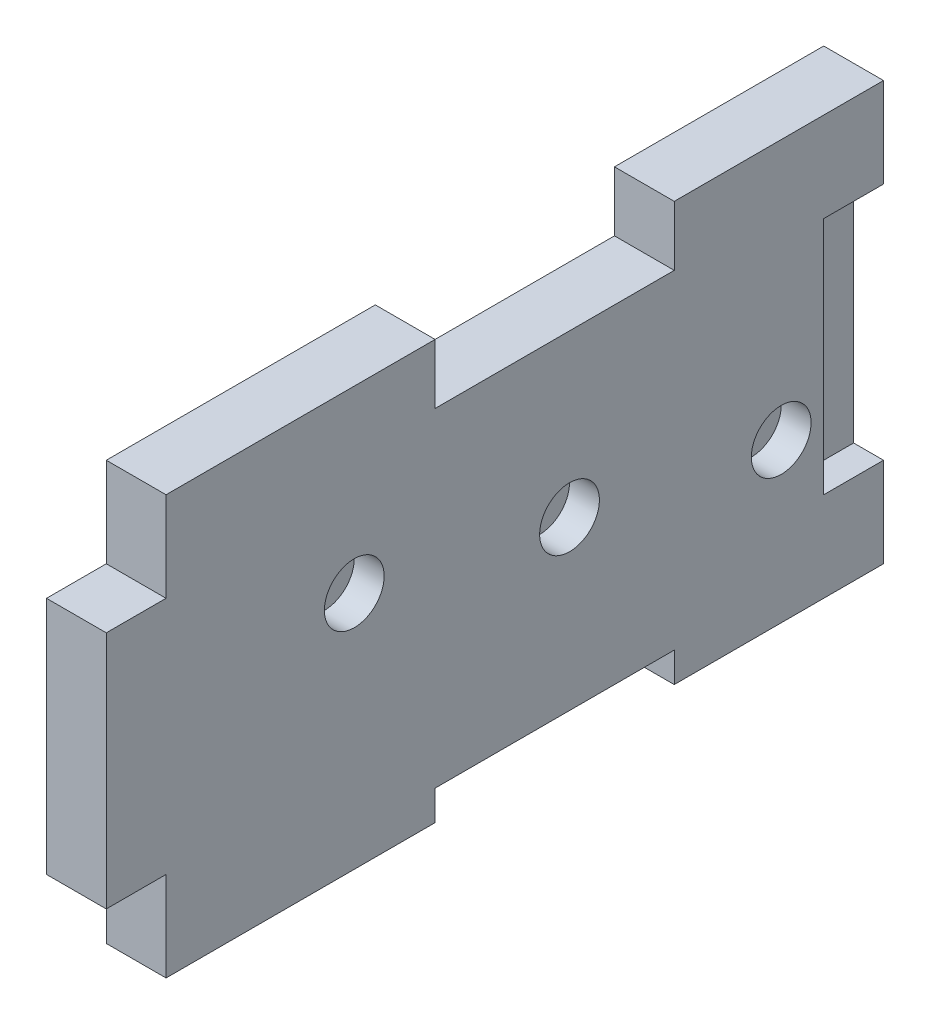
SolidWorks part; units mm, degrees
ref_plane "Front Plane" through (0, 0, 0) normal (0, 0, 1) x (1, 0, 0)
ref_plane "Top Plane" through (0, 0, 0) normal (0, 1, 0) x (1, 0, 0)
ref_plane "Right Plane" through (0, 0, 0) normal (1, 0, 0) x (0, 0, -1)
sketch "Sketch1" plane through (0, 0, 0) normal (1, 0, 0) x (0, 0, -1)
  line L1 (-130, 70) -> (0, 70)
  line L2 (-130, 70) -> (-130, 0)
  line L3 (-130, 0) -> (0, 0)
  line L4 (0, 70) -> (0, 0)
  line L5 (-130, 70) -> (-120, 70)
  line L6 (-130, 70) -> (-130, 55)
  line L7 (-130, 55) -> (-120, 55)
  line L8 (-120, 70) -> (-120, 55)
  line L9 (-130, 0) -> (-120, 0)
  line L10 (-130, 0) -> (-130, 15)
  line L11 (-130, 15) -> (-120, 15)
  line L12 (-120, 0) -> (-120, 15)
  line L13 (0, 70) -> (-10, 70)
  line L14 (0, 70) -> (0, 55)
  line L17 (0, 0) -> (-10, 0)
  line L18 (0, 0) -> (0, 15)
  line L21 (-75, 70) -> (-35, 70)
  line L22 (-75, 70) -> (-75, 60)
  line L23 (-75, 60) -> (-35, 60)
  line L24 (-35, 70) -> (-35, 60)
  line L25 (-75, 0) -> (-35, 0)
  line L26 (-75, 0) -> (-75, 5)
  line L27 (-75, 5) -> (-35, 5)
  line L28 (-35, 0) -> (-35, 5)
  dimension "D1" = 130
  dimension "D2" = 70
  dimension "D3" = 10
  dimension "D4" = 15
  dimension "D5" = 10
  dimension "D6" = 15
  dimension "D11" = 10
  dimension "D12" = 40
  dimension "D13" = 55
  dimension "D14" = 55
  dimension "D15" = 40
  dimension "D16" = 5
extrude "Boss-Extrude1" add sketch "Sketch1" along normal blind 5
sketch "Sketch2" plane through (5, 0, 0) normal (1, 0, 0) x (0, 0, -1)
  line L1 (-130, 55) -> (-130, 15) construction
  line L2 (-75, 5) -> (-35, 5) construction
  circle A0 centre (-88.52, 40) radius 5
  dimension "D3" = 10
  dimension "D1" = 35
  dimension "D2" = 41.48
sketch "Sketch5" plane through (0, 0, 0) normal (-1, 0, 0) x (0, 0, 1)
  line L0 (75, 5) -> (35, 5) construction
  line L1 (0, 70) -> (0, 0) construction
  line L3 (120, 70) -> (120, 55) construction
  circle A0 centre (52.52, 33) radius 5
  circle A1 centre (17.1117, 26.5) radius 5
  dimension "D1" = 10
  dimension "D4" = 10
  dimension "D6" = 17.1117
  dimension "D2" = 28
  dimension "D3" = 67.48
  dimension "D5" = 36
extrude "Cut-Extrude4" cut sketch "Sketch5" against normal blind 5 contours A1 | A0
extrude "Cut-Extrude5" cut sketch "Sketch2" against normal blind 5
sketch "Sketch6" plane through (0, 0, 0) normal (-1, 0, 0) x (0, 0, 1)
  line L40 (35, 0) -> (35, 5)
  line L41 (35, 5) -> (75, 5)
  line L42 (75, 5) -> (75, 0)
  line L43 (75, 0) -> (120, 0)
  line L44 (120, 0) -> (120, 15)
  line L45 (120, 15) -> (130, 15)
  line L46 (130, 15) -> (130, 55)
  line L47 (130, 55) -> (120, 55)
  line L48 (120, 55) -> (120, 70)
  line L49 (120, 70) -> (75, 70)
  line L50 (75, 70) -> (75, 60)
  line L51 (75, 60) -> (35, 60)
  line L52 (35, 60) -> (35, 70)
  line L53 (35, 70) -> (0, 70)
  line L56 (0, 70) -> (0, 0)
  line L59 (0, 0) -> (35, 0)
  line L60 (35, 0) -> (35, 5)
  line L61 (35, 5) -> (75, 5)
  line L62 (75, 5) -> (75, 0)
  line L63 (75, 0) -> (120, 0)
  line L64 (120, 0) -> (120, 15)
  line L65 (120, 15) -> (130, 15)
  line L66 (130, 15) -> (130, 55)
  line L67 (130, 55) -> (120, 55)
  line L68 (120, 55) -> (120, 70)
  line L69 (120, 70) -> (75, 70)
  line L70 (75, 70) -> (75, 60)
  line L71 (75, 60) -> (35, 60)
  line L72 (35, 60) -> (35, 70)
  line L73 (35, 70) -> (0, 70)
  line L76 (0, 70) -> (0, 0)
  line L79 (0, 0) -> (35, 0)
  dimension "D1" = 0
extrude "Boss-Extrude2" add sketch "Sketch6" along normal blind 5
sketch "Sketch7" plane through (5, 0, 0) normal (1, 0, 0) x (0, 0, -1)
  line L0 (0, 70) -> (0, 0) construction
  line L1 (0, 55) -> (-10, 55)
  line L2 (0, 55) -> (0, 15)
  line L3 (0, 15) -> (-10, 15)
  line L4 (-10, 55) -> (-10, 15)
  point P4 (0, 35)
  point P7 (0, 35)
  dimension "D1" = 10
  dimension "D2" = 40
extrude "Cut-Extrude6" cut sketch "Sketch7" against normal blind 5
